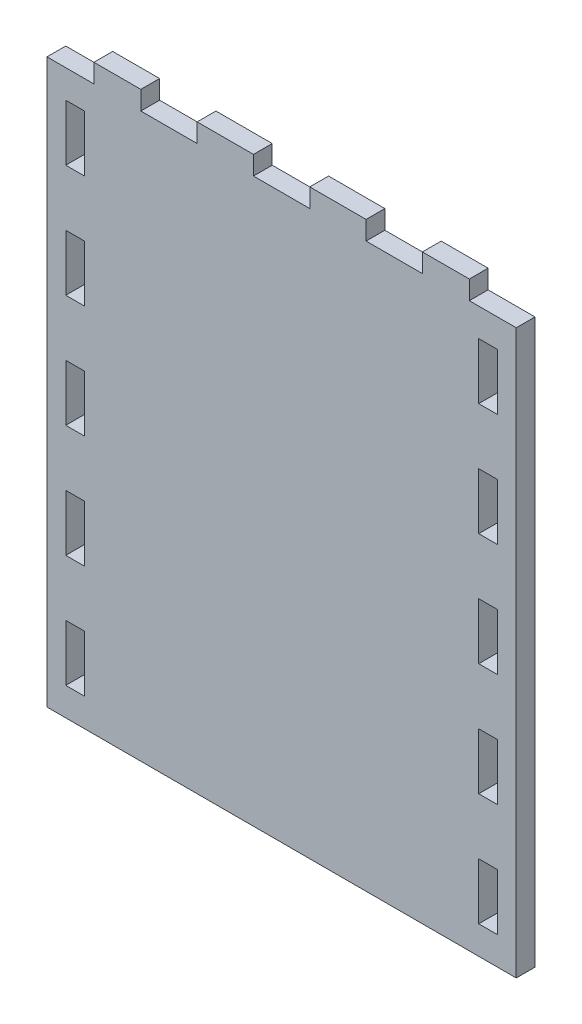
SolidWorks part; units mm, degrees
material "PVC 0.007 plastifié"
ref_plane "Plan de face" through (0, 0, 0) normal (0, 0, 1) x (1, 0, 0)
ref_plane "Plan de dessus" through (0, 0, 0) normal (0, 1, 0) x (1, 0, 0)
ref_plane "Plan de droite" through (0, 0, 0) normal (1, 0, 0) x (0, 0, -1)
sketch "Esquisse1" plane through (0, 0, 0) normal (0, 0, 1) x (1, 0, 0)
  line L1 (-53.6517, 84.4944) -> (71.3483, 84.4944)
  line L2 (-53.6517, 84.4944) -> (-53.6517, -70.5056)
  line L3 (-53.6517, -70.5056) -> (71.3483, -70.5056)
  line L4 (71.3483, 84.4944) -> (71.3483, -70.5056)
  dimension "D1" = 155
  dimension "D2" = 125
extrude "Boss.-Extru.2" add sketch "Esquisse1" along normal blind 5
sketch "Esquisse3" plane through (0, 0, 0) normal (0, 0, -1) x (-1, 0, 0)
  line L0 (53.6517, -70.5056) -> (-71.3483, -70.5056) construction
  line L1 (-66.3483, -63.0056) -> (-61.3483, -63.0056)
  line L2 (-66.3483, -63.0056) -> (-66.3483, -48.0056)
  line L3 (-66.3483, -48.0056) -> (-61.3483, -48.0056)
  line L4 (-61.3483, -63.0056) -> (-61.3483, -48.0056)
  line L5 (-71.3483, -70.5056) -> (-71.3483, 84.4944) construction
  line L7 (53.6517, 84.4944) -> (53.6517, -70.5056) construction
  line L8 (-66.3483, -33.0056) -> (-61.3483, -33.0056)
  line L9 (-66.3483, -33.0056) -> (-66.3483, -18.0056)
  line L10 (-66.3483, -18.0056) -> (-61.3483, -18.0056)
  line L11 (-61.3483, -33.0056) -> (-61.3483, -18.0056)
  line L12 (-66.3483, -3.0056) -> (-61.3483, -3.0056)
  line L13 (-66.3483, -3.0056) -> (-66.3483, 11.9944)
  line L14 (-66.3483, 11.9944) -> (-61.3483, 11.9944)
  line L15 (-61.3483, -3.0056) -> (-61.3483, 11.9944)
  line L16 (-66.3483, 26.9944) -> (-61.3483, 26.9944)
  line L17 (-66.3483, 26.9944) -> (-66.3483, 41.9944)
  line L18 (-66.3483, 41.9944) -> (-61.3483, 41.9944)
  line L19 (-61.3483, 26.9944) -> (-61.3483, 41.9944)
  line L20 (-66.3483, 56.9944) -> (-61.3483, 56.9944)
  line L21 (-66.3483, 56.9944) -> (-66.3483, 71.9944)
  line L22 (-66.3483, 71.9944) -> (-61.3483, 71.9944)
  line L23 (-61.3483, 56.9944) -> (-61.3483, 71.9944)
  line L24 (43.6517, -63.0056) -> (48.6517, -63.0056)
  line L25 (43.6517, -63.0056) -> (43.6517, -48.0056)
  line L26 (43.6517, -48.0056) -> (48.6517, -48.0056)
  line L27 (48.6517, -63.0056) -> (48.6517, -48.0056)
  line L28 (43.6517, 26.9944) -> (48.6517, 26.9944)
  line L29 (43.6517, -33.0056) -> (48.6517, -33.0056)
  line L30 (43.6517, -33.0056) -> (43.6517, -18.0056)
  line L31 (43.6517, -18.0056) -> (48.6517, -18.0056)
  line L32 (48.6517, -33.0056) -> (48.6517, -18.0056)
  line L33 (43.6517, -3.0056) -> (48.6517, -3.0056)
  line L34 (43.6517, -3.0056) -> (43.6517, 11.9944)
  line L35 (43.6517, 11.9944) -> (48.6517, 11.9944)
  line L36 (48.6517, -3.0056) -> (48.6517, 11.9944)
  line L37 (43.6517, 26.9944) -> (43.6517, 41.9944)
  line L38 (43.6517, 41.9944) -> (48.6517, 41.9944)
  line L39 (48.6517, 26.9944) -> (48.6517, 41.9944)
  line L40 (48.6517, 56.9944) -> (43.6517, 56.9944)
  line L41 (48.6517, 56.9944) -> (48.6517, 71.9944)
  line L42 (48.6517, 71.9944) -> (43.6517, 71.9944)
  line L43 (43.6517, 56.9944) -> (43.6517, 71.9944)
  dimension "D1" = 5
  dimension "D2" = 15
  dimension "D3" = 7.5
  dimension "D4" = 5
  dimension "D5" = 5
  dimension "D6" = 15
  dimension "D7" = 5
  dimension "D8" = 15
  dimension "D9" = 5
  dimension "D10" = 15
  dimension "D11" = 5
  dimension "D12" = 15
  dimension "D13" = 5
  dimension "D14" = 15
  dimension "D15" = 15
  dimension "D16" = 5
  dimension "D17" = 15
  dimension "D18" = 5
  dimension "D19" = 15
  dimension "D20" = 5
  dimension "D21" = 5
  dimension "D22" = 15
  dimension "D23" = 7.5
  dimension "D24" = 5
  dimension "D25" = 5
  dimension "D26" = 15
  dimension "D27" = 5
  dimension "D28" = 5
  dimension "D29" = 15
  dimension "D30" = 5
  dimension "D31" = 15
  dimension "D32" = 15
  dimension "D33" = 5
  dimension "D34" = 15
  dimension "D35" = 5
  dimension "D36" = 15
  dimension "D37" = 5
  dimension "D38" = 5
  dimension "D39" = 15
extrude "Enlèv. mat.-Extru.1" cut sketch "Esquisse3" against normal blind 5
sketch "Esquisse4" plane through (0, 0, 0) normal (0, 0, -1) x (-1, 0, 0)
  line L0 (-71.3483, 84.4944) -> (53.6517, 84.4944) construction
  line L1 (-71.3483, 84.4944) -> (-58.8483, 84.4944)
  line L2 (-71.3483, 84.4944) -> (-71.3483, 79.4944)
  line L3 (-71.3483, 79.4944) -> (-58.8483, 79.4944)
  line L4 (-58.8483, 84.4944) -> (-58.8483, 79.4944)
  line L5 (53.6517, 84.4944) -> (41.1517, 84.4944)
  line L6 (53.6517, 84.4944) -> (53.6517, 79.4944)
  line L7 (53.6517, 79.4944) -> (41.1517, 79.4944)
  line L8 (41.1517, 84.4944) -> (41.1517, 79.4944)
  line L9 (-46.3483, 84.4944) -> (-31.3483, 84.4944)
  line L10 (-46.3483, 84.4944) -> (-46.3483, 79.4944)
  line L11 (-46.3483, 79.4944) -> (-31.3483, 79.4944)
  line L12 (-31.3483, 84.4944) -> (-31.3483, 79.4944)
  line L14 (-16.3483, 84.4944) -> (-1.3483, 84.4944)
  line L15 (-16.3483, 84.4944) -> (-16.3483, 79.4944)
  line L16 (-16.3483, 79.4944) -> (-1.3483, 79.4944)
  line L17 (-1.3483, 84.4944) -> (-1.3483, 79.4944)
  line L18 (13.6517, 86.864) -> (13.2456, 86.864)
  line L19 (13.6517, 86.864) -> (13.6517, 84.4944)
  line L20 (13.6517, 84.4944) -> (13.2456, 84.4944)
  line L21 (13.2456, 86.864) -> (13.2456, 84.4944)
  line L22 (13.6517, 84.4944) -> (28.6517, 84.4944)
  line L23 (13.6517, 84.4944) -> (13.6517, 79.4944)
  line L24 (13.6517, 79.4944) -> (28.6517, 79.4944)
  line L25 (28.6517, 84.4944) -> (28.6517, 79.4944)
  line M43 (53.6517, 84.4944) -> (-71.3483, 84.4944)
  line M44 (-71.3483, 84.4944) -> (-71.3483, -70.5056)
  dimension "D1" = 5
  dimension "D2" = 12.5
  dimension "D3" = 12.5
  dimension "D4" = 15
  dimension "D5" = 12.5
  dimension "D6" = 5
  dimension "D7" = 15
  dimension "D8" = 15
  dimension "D9" = 15
  dimension "D10" = 5
  dimension "D11" = 15
extrude "Enlèv. mat.-Extru.2" cut sketch "Esquisse4" against normal blind 50 contours L12 L10 L11 M43 | L4 L3 M43 M44 | L16 L17 L14 L15 | L23 L24 L25 L22 | L7 L8 L5 L6
